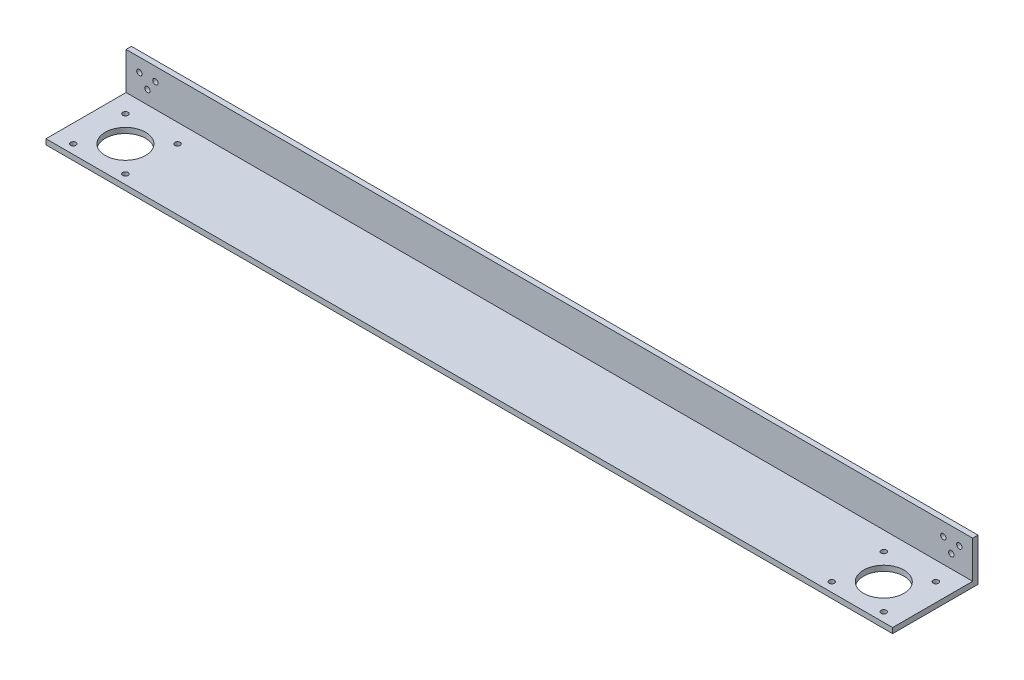
SolidWorks part; units mm, degrees
ref_plane "Front Plane" through (0, 0, 0) normal (0, 0, 1) x (1, 0, 0)
ref_plane "Top Plane" through (0, 0, 0) normal (0, 1, 0) x (1, 0, 0)
ref_plane "Right Plane" through (0, 0, 0) normal (1, 0, 0) x (0, 0, -1)
sketch "Sketch1" plane through (0, 0, 0) normal (1, 0, 0) x (0, 0, -1)
  line L0 (0, 0) -> (-50.8, 0)
  line L1 (-50.8, 0) -> (-50.8, 3.175)
  line L2 (-50.8, 3.175) -> (-3.175, 3.175)
  line L3 (-3.175, 3.175) -> (-3.175, 25.4)
  line L4 (-3.175, 25.4) -> (0, 25.4)
  line L5 (0, 25.4) -> (0, 0)
  dimension "LHeight" = 25.4
  dimension "LWidth" = 50.8
  dimension "LMaterialThickness" = 3.175
  dimension "D1" = 47.625
  dimension "D2" = 22.225
  dimension "D3" = 3.175
extrude "Boss-Extrude1" add sketch "Sketch1" along normal blind 503.65
sketch "TopHoles-Sketch2" plane through (0, 3.175, 0) normal (0, 1, 0) x (1, 0, 0)
  line L0 (503.65, 0) -> (0, 0) construction
  line L1 (503.65, -50.8) -> (0, -50.8) construction
  line L2 (0, -3.175) -> (0, -50.8) construction
  line L3 (503.65, -3.175) -> (503.65, -50.8) construction
  circle A0 centre (26.25, -29.8) radius 12
  circle A1 centre (477.4, -29.8) radius 12
  circle A2 centre (10.75, -14.3) radius 1.5875
  circle A3 centre (41.75, -14.3) radius 1.5875
  circle A4 centre (461.9, -14.3) radius 1.5875
  circle A5 centre (492.9, -14.3) radius 1.5875
  circle A6 centre (10.75, -45.3) radius 1.5875
  circle A7 centre (41.75, -45.3) radius 1.5875
  circle A8 centre (461.9, -45.3) radius 1.5875
  circle A9 centre (492.9, -45.3) radius 1.5875
  dimension "D9" = 3.175
  dimension "D10" = 24
  dimension "D3" = 31
  dimension "D4" = 15.5
  dimension "D5" = 15.5
  dimension "D6" = 31
  dimension "D7" = 15.5
  dimension "D13" = 26.25
  dimension "D8" = 31
  dimension "D11" = 26.25
  dimension "D2" = 5.5
  dimension "D12" = 14.3
extrude "TopHoles-Cut-Extrude1" cut sketch "TopHoles-Sketch2" against normal through all
sketch "BackSideHoles-Sketch3" plane through (0, 0, 0) normal (0, 0, -1) x (-1, 0, 0)
  line L1 (-503.65, 25.4) -> (0, 25.4) construction
  line L2 (0, 0) -> (0, 25.4) construction
  line L3 (-503.65, 0) -> (-503.65, 25.4) construction
  circle A0 centre (-495.7125, 17.4625) radius 1.5875
  circle A1 centre (-486.1875, 17.4625) radius 1.5875
  circle A3 centre (-490.95, 11.1125) radius 1.5875
  circle A4 centre (-12.7, 11.1125) radius 1.5875
  circle A6 centre (-17.4625, 17.4625) radius 1.5875
  circle A7 centre (-7.9375, 17.4625) radius 1.5875
  dimension "D7" = 3.175
  dimension "D4" = 11.1125
  dimension "D3" = 7.9375
  dimension "D1" = 7.9375
  dimension "D2" = 17.4625
  dimension "D6" = 17.4625
  dimension "D5" = 7.9375
  dimension "D8" = 12.7
  dimension "D9" = 12.7
extrude "BackSideHoles-Cut-Extrude2" cut sketch "BackSideHoles-Sketch3" against normal through all
equation "\"MidBackRailWidth\"= 2.00in"
equation "\"MidBackRailHeight\"= 1.00in"
equation "\"RailThickness\"= .125in'Spec"
equation "\"SideRailHoleY1FromEdge\"= \"HoleOffsetFromEdge\""
equation "\"SideRailHoleX1FromSide\"= \"HoleOffsetFromSide\""
equation "\"StepperHoleDiameter\"= 24mm"
equation "\"StepperMountingHoleDiameter\"= 3.175mm"
equation "\"StepperMountingHoleDistance\"= 31mm'Spec"
equation "\"VSWidth\"= 1.25in'Spec"
equation "\"StepperMountingHoleOffsetFromLeftRightEdge\"= \"StepperMountingHoleOffsetFromItsSide\""
equation "\"HoleOffsetFromEdge\"= \"RailThickness\" * 2.5"
equation "\"HoleOffsetFromSide\"= \"RailThickness\" * 3.5"
equation "\"StepperMountingHoleOffsetFromItsSide\"= 5.5mm'Spec"
equation "\"SideRailHoleX2FromSide\"= \"VSWidth\" - \"HoleOffsetFromEdge\" - \"RailThickness\"'Equals 20.6375"
equation "\"FasteningHoleDiameter\"= .125in"
equation "\"SideRailHoleY2FromSide\"= \"HoleOffsetFromSide\""
equation "\"FrontBackRailLength\"= 510mm"
equation "\"LHeight@Sketch1\"=\"MidBackRailHeight\""
equation "\"LWidth@Sketch1\"=\"MidBackRailWidth\""
equation "\"D3@TopHoles-Sketch2\" = \"StepperMountingHoleDistance\""
equation "\"D4@TopHoles-Sketch2\" = \"StepperMountingHoleDistance\" / 2"
equation "\"D5@TopHoles-Sketch2\" = \"StepperMountingHoleDistance\" / 2"
equation "\"D6@TopHoles-Sketch2\" = \"StepperMountingHoleDistance\""
equation "\"D7@TopHoles-Sketch2\" = \"StepperMountingHoleDistance\" / 2"
equation "\"D9@TopHoles-Sketch2\" = \"StepperMountingHoleDiameter\""
equation "\"D10@TopHoles-Sketch2\" = \"StepperHoleDiameter\""
equation "\"D4@BackSideHoles-Sketch3\" = \"SideRailHoleY2FromSide\""
equation "\"D7@BackSideHoles-Sketch3\" = \"FasteningHoleDiameter\""
equation "\"D1@Boss-Extrude1\"= \"MidBackRailLength\""
equation "\"D3@BackSideHoles-Sketch3\"=\"SideRailHoleY1FromEdge\""
equation "\"D1@BackSideHoles-Sketch3\"=\"SideRailHoleX1FromSide\" - \"RailThickness\""
equation "\"D2@BackSideHoles-Sketch3\"=\"SideRailHoleX2FromSide\" - \"RailThickness\""
equation "\"D6@BackSideHoles-Sketch3\"=\"SideRailHoleX2FromSide\" - \"RailThickness\""
equation "\"D5@BackSideHoles-Sketch3\"=\"SideRailHoleX1FromSide\" - \"RailThickness\""
equation "\"StepperHoleToAlignHorizontallyWithGantryBlock\"= \"LinearGBWithRailDepth\" + \"GABDistanceFromBackToFirstPulley\"'Equals 26.25"
equation "\"D13@TopHoles-Sketch2\"=\"StepperHoleToAlignHorizontallyWithGantryBlock\" "
equation "\"D8@TopHoles-Sketch2\"=\"StepperMountingHoleDistance\""
equation "\"D11@TopHoles-Sketch2\"=\"StepperHoleToAlignHorizontallyWithGantryBlock\" "
equation "\"LinearGBWithRailDepth\"= 12.75mm'Spec"
equation "\"GABDistanceFromBackToFirstPulley\"= 13.5mm"
equation "\"MidBackRailLength\"= \"FrontBackRailLength\" - \"RailThickness\" * 2'MidBackRail buts up against MidSideRail"
equation "\"VSMidSideRailHoleXFromSideToCenter\"= \"RailThickness\" * 6"
equation "\"D8@BackSideHoles-Sketch3\"=\"VSMidSideRailHoleXFromSideToCenter\"- \"RailThickness\" - \"RailThickness\""
equation "\"D9@BackSideHoles-Sketch3\"=\"VSMidSideRailHoleXFromSideToCenter\" - \"RailThickness\" - \"RailThickness\""
equation "\"D2@TopHoles-Sketch2\"=\"StepperMountingHoleOffsetFromLeftRightEdge\""
